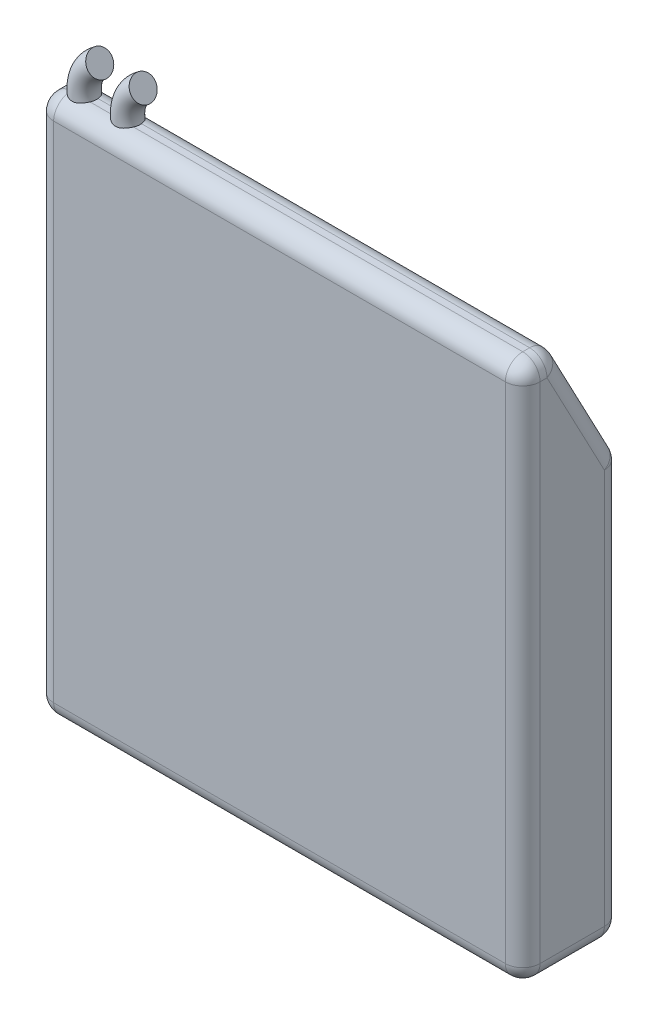
SolidWorks part; units mm, degrees
ref_plane "Front Plane" through (0, 0, 0) normal (0, 0, 1) x (1, 0, 0)
ref_plane "Top Plane" through (0, 0, 0) normal (0, 1, 0) x (1, 0, 0)
ref_plane "Right Plane" through (0, 0, 0) normal (1, 0, 0) x (0, 0, -1)
sketch "Sketch1" plane through (0, 0, 0) normal (1, 0, 0) x (0, 0, -1)
  line L0 (0, 0) -> (0, 31)
  line L1 (0, 31) -> (2, 31)
  line L2 (2, 31) -> (5.7, 24)
  line L3 (5.7, 24) -> (5.7, 0)
  line L4 (5.7, 0) -> (0, 0)
  dimension "D1" = 5.7
  dimension "D2" = 31
  dimension "D3" = 2
  dimension "D4" = 24
extrude "Boss-Extrude1" add sketch "Sketch1" along normal blind 28 contours L4 L0 L1 L2 L3
fillet "Fillet1" radius 1 15 edges at (14, 24, -5.7) (14, 31, -2) (14, 31, 0) (14, 0, 0) (14, 0, -5.7) (28, 27.5, -3.85) (28, 31, -1) (28, 15.5, 0) (28, 0, -2.85) (28, 12, -5.7) (0, 27.5, -3.85) (0, 31, -1) (0, 15.5, 0) (0, 0, -2.85) (0, 12, -5.7)
ref_plane "Plane1" through (0, 0, -1.3) normal (0, 0, 1) x (1, 0, 0)
sketch "Sketch2" plane through (0, 0, -1.3) normal (0, 0, 1) x (1, 0, 0)
  arc A0 (2.3532, 32.9187) -> (2.2979, 29.4919) centre (3.5698, 31.1852) ccw
  point P3 (0, 0)
  point P4 (3.0357, 31.6224)
  point P6 (2.2938, 29.3661)
  point P7 (3.5698, 31.1852)
sweep "Sweep1" add path "Sketch2" circular profile diameter 1.4 parameters "D3"=1.4
pattern_linear "LPattern1" count 2 spacing 2.5 along (1, 0, 0) of "Sweep1"
